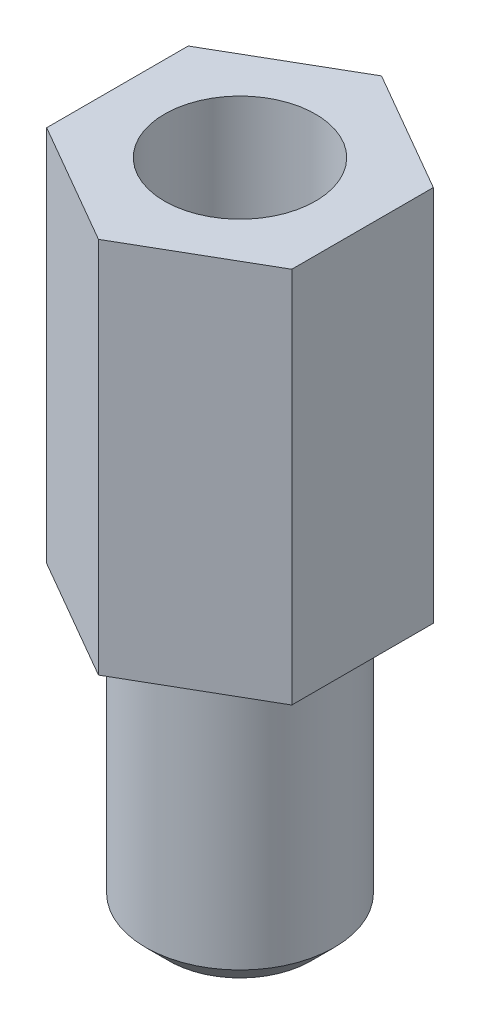
SolidWorks part; units mm, degrees
material "Автоматная латунь, UNS C36000"
ref_plane "Спереди" through (0, 0, 0) normal (0, 0, 1) x (1, 0, 0)
ref_plane "Сверху" through (0, 0, 0) normal (0, 1, 0) x (1, 0, 0)
ref_plane "Справа" through (0, 0, 0) normal (1, 0, 0) x (0, 0, -1)
sketch "Эскиз1" plane through (0, 0, 0) normal (0, 1, 0) x (1, 0, 0)
  line L7 (0, 1.5) -> (-1.299, 0.75)
  line L8 (-1.299, 0.75) -> (-1.299, -0.75)
  line L9 (-1.299, -0.75) -> (0, -1.5)
  line L10 (0, -1.5) -> (1.299, -0.75)
  line L11 (1.299, -0.75) -> (1.299, 0.75)
  line L12 (1.299, 0.75) -> (0, 1.5)
  circle A1 centre (0, 0) radius 1.5
  circle A2 centre (0, 0) radius 1.299 construction
  dimension "D1" = 3
extrude "Бобышка-Вытянуть1" add sketch "Эскиз1" along normal blind 4 contours L11 L12 L7 L8 L9 L10
sketch "Эскиз4" plane through (0, 0, 0) normal (0, -1, 0) x (1, 0, 0)
  circle A0 centre (0, 0) radius 1
extrude "Бобышка-Вытянуть2" add sketch "Эскиз4" along normal blind 3
chamfer "Фаска1" distance 0.25 angle 45 1 edges at (0, -3, -1)
hole_wizard "Отверстие обработанное метчиком M23" positions "Эскиз5" profile "Эскиз6" tap size "M2" standard "ISO"
sketch "Эскиз5" plane through (0, 4, 0) normal (0, 1, 0) x (1, 0, 0)
  point P0 (0, 0)
sketch "Эскиз6" plane through (0, 4, 0) normal (1, 0, 0) x (0, 0, 1)
  line L0 (0, 0) -> (0, 4.4807)
  line L1 (0, 4.4807) -> (0.8, 4)
  line L2 (0.8, 4) -> (0.8, 0)
  line L5 (0.8, 0) -> (0, 0)
  line L10 (0, 4.4807) -> (-0.8, 4) construction
  line L11 (0, -6.35) -> (0, 107.95) construction
  dimension "Диаметр сверла" = 1.6
  dimension "Глубина сверла" = 4
  dimension "Угол заточки сверла" = 118
cosmetic thread "Отверстие резьбы1" parameters "D1"=4, "D2"=2
